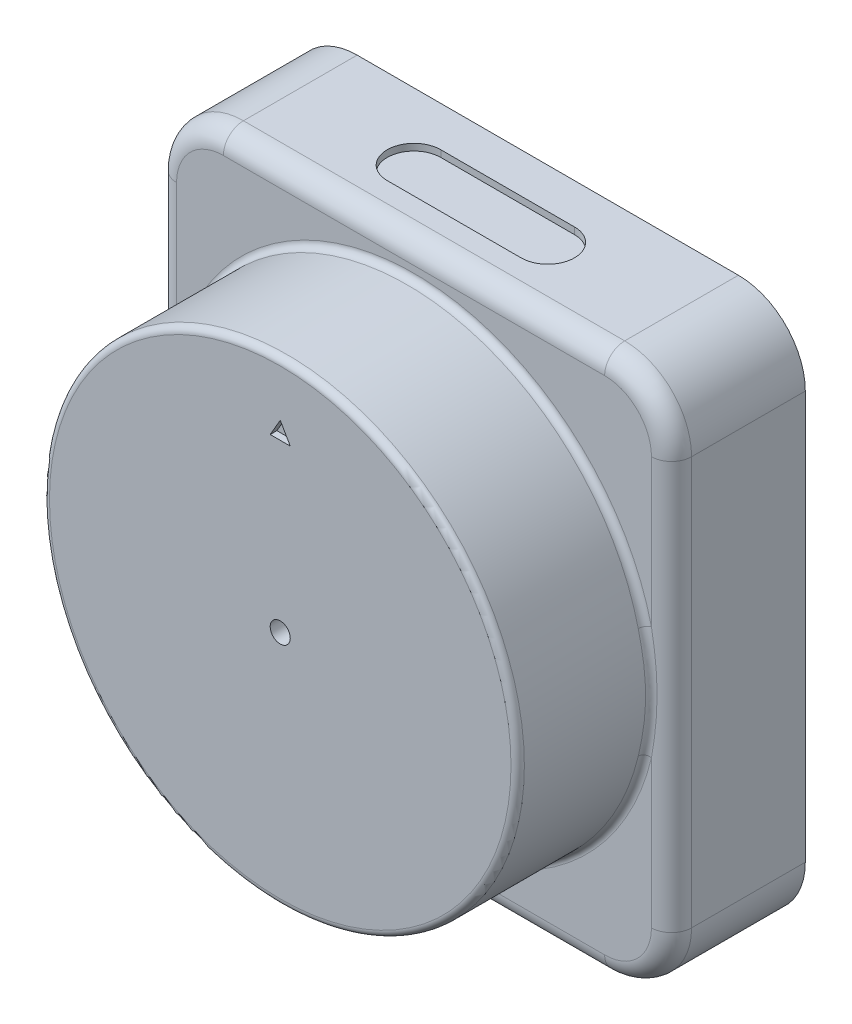
SolidWorks part; units mm, degrees
ref_plane "前视基准面" through (0, 0, 0) normal (0, 0, 1) x (1, 0, 0)
ref_plane "上视基准面" through (0, 0, 0) normal (0, 1, 0) x (1, 0, 0)
ref_plane "右视基准面" through (0, 0, 0) normal (1, 0, 0) x (0, 0, -1)
sketch "草图1" plane through (0, 0, 0) normal (0, 0, 1) x (1, 0, 0)
  line L1 (-38.5, -40.5) -> (38.5, -40.5)
  line L2 (-38.5, -40.5) -> (-38.5, 40.5)
  line L3 (-38.5, 40.5) -> (38.5, 40.5)
  line L4 (38.5, -40.5) -> (38.5, 40.5)
  line L5 (-38.5, -40.5) -> (38.5, 40.5) construction
  line L6 (-38.5, 40.5) -> (38.5, -40.5) construction
  point P0 (0, 0)
  dimension "D1" = 81
  dimension "D2" = 77
extrude "凸台-拉伸1" add sketch "草图1" along normal blind 20
fillet "圆角1" radius 10 4 edges at (38.5, -40.5, 10) (38.5, 40.5, 10) (-38.5, -40.5, 10) (-38.5, 40.5, 10)
fillet "圆角2" radius 3 8 edges at (35.5711, 37.5711, 20) (38.5, 0, 20) (35.5711, -37.5711, 20) (0, -40.5, 20) (-35.5711, -37.5711, 20) (-38.5, 0, 20) (-35.5711, 37.5711, 20) (0, 40.5, 20)
sketch "草图3" plane through (0, 0, 20) normal (0, 0, 1) x (1, 0, 0)
  circle A1 centre (0, 0) radius 35.5
extrude "凸台-拉伸2" add sketch "草图3" along normal blind 20
fillet "圆角3" radius 1 3 edges at (0, 35.5, 20) (0, -35.5, 20) (35.5, 0, 40)
sketch "草图4" plane through (0, 0, 40) normal (0, 0, 1) x (1, 0, 0)
  circle A0 centre (0, 0) radius 1.5
  dimension "D1" = 3
extrude "切除-拉伸1" cut sketch "草图4" against normal blind 10
sketch "草图5" plane through (0, 40.5, 0) normal (0, 1, 0) x (1, 0, 0)
  line L3 (0, -10) -> (10, -10) construction
  line L4 (-10, -6) -> (10, -6)
  line L5 (-10, -14) -> (10, -14)
  arc A0 (-10, -6) -> (-10, -14) centre (-10, -10) ccw
  arc A1 (10, -14) -> (10, -6) centre (10, -10) ccw
  point P3 (0, -10)
  dimension "D4" = 4
  dimension "D2" = 10
  dimension "D3" = 10
extrude "切除-拉伸2" cut sketch "草图5" against normal blind 1
sketch "草图6" plane through (0, 0, 40) normal (0, 0, 1) x (1, 0, 0)
  line L1 (0, 27.4725) -> (-1.5, 24.8744)
  line L2 (0, 27.4725) -> (1.5, 24.8744)
  line L3 (-1.5, 24.8744) -> (1.5, 24.8744)
  dimension "D2" = 3
extrude "切除-拉伸3" cut sketch "草图6" against normal blind 1
